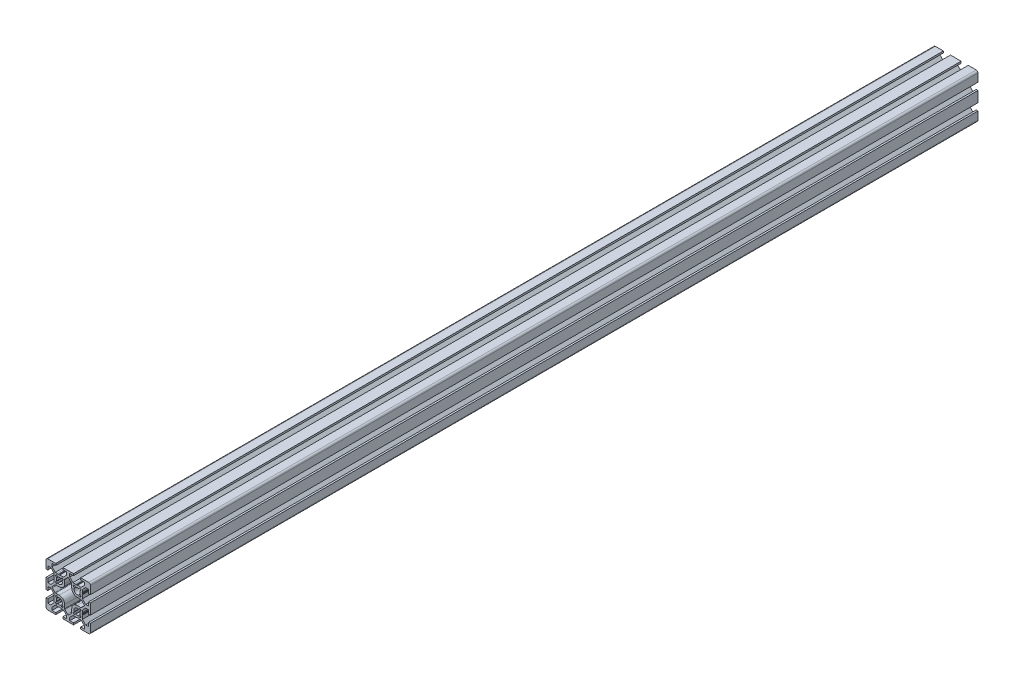
SolidWorks part; units mm, degrees
ref_plane "Front Plane" through (0, 0, 0) normal (0, 0, 1) x (1, 0, 0)
ref_plane "Top Plane" through (0, 0, 0) normal (0, 1, 0) x (1, 0, 0)
ref_plane "Right Plane" through (0, 0, 0) normal (1, 0, 0) x (0, 0, -1)
ref_plane "Plane1" through (0, 0, 0) normal (0, 0, 1) x (1, 0, 0)
sketch "Sketch1" plane through (0, 0, 0) normal (0, 0, 1) x (1, 0, 0)
  line L0 (-25, 23) -> (-25, 14)
  line L1 (-25, 14) -> (-23, 14)
  line L2 (-23, 14) -> (-23, 18.25)
  line L3 (-23, 18.25) -> (-19.6642, 18.25)
  line L4 (-19.6642, 18.25) -> (-16, 14.5858)
  line L5 (-16, 14.5858) -> (-16, 10.6536)
  line L6 (-15.933, 10.4036) -> (-15.7, 10)
  line L7 (-15.7, 10) -> (-15.933, 9.5964)
  line L8 (-15.933, 9.0964) -> (-15.751, 8.7811)
  line L9 (-15.751, 8.7811) -> (-16, 7.5)
  line L10 (-16, 7.5) -> (-16, 5.4142)
  line L11 (-16, 5.4142) -> (-19.6642, 1.75)
  line L12 (-19.6642, 1.75) -> (-23, 1.75)
  line L13 (-23, 1.75) -> (-23, 6)
  line L14 (-23, 6) -> (-25, 6)
  line L15 (-25, 6) -> (-25, -6)
  line L16 (-25, -6) -> (-23, -6)
  line L17 (-23, -6) -> (-23, -1.75)
  line L18 (-23, -1.75) -> (-19.6642, -1.75)
  line L19 (-19.6642, -1.75) -> (-16, -5.4142)
  line L20 (-16, -5.4142) -> (-16, -9.3464)
  line L21 (-15.933, -9.5964) -> (-15.7, -10)
  line L22 (-15.7, -10) -> (-15.933, -10.4036)
  line L23 (-15.933, -10.9036) -> (-15.751, -11.2189)
  line L24 (-15.751, -11.2189) -> (-16, -12.5)
  line L25 (-16, -12.5) -> (-16, -14.5858)
  line L26 (-16, -14.5858) -> (-19.6642, -18.25)
  line L27 (-19.6642, -18.25) -> (-23, -18.25)
  line L28 (-23, -18.25) -> (-23, -14)
  line L29 (-23, -14) -> (-25, -14)
  line L30 (-25, -14) -> (-25, -23)
  line L31 (-23, -25) -> (-14, -25)
  line L32 (-14, -25) -> (-14, -23)
  line L33 (-14, -23) -> (-18.25, -23)
  line L34 (-18.25, -23) -> (-18.25, -19.6642)
  line L35 (-18.25, -19.6642) -> (-14.5858, -16)
  line L36 (-14.5858, -16) -> (-10.6536, -16)
  line L37 (-10.4036, -15.933) -> (-10, -15.7)
  line L38 (-10, -15.7) -> (-9.5964, -15.933)
  line L39 (-9.0964, -15.933) -> (-8.7811, -15.751)
  line L40 (-8.7811, -15.751) -> (-7.5, -16)
  line L41 (-7.5, -16) -> (-5.4142, -16)
  line L42 (-5.4142, -16) -> (-1.75, -19.6642)
  line L43 (-1.75, -19.6642) -> (-1.75, -23)
  line L44 (-1.75, -23) -> (-6, -23)
  line L45 (-6, -23) -> (-6, -25)
  line L46 (-6, -25) -> (6, -25)
  line L47 (6, -25) -> (6, -23)
  line L48 (6, -23) -> (1.75, -23)
  line L49 (1.75, -23) -> (1.75, -19.6642)
  line L50 (1.75, -19.6642) -> (5.4142, -16)
  line L51 (5.4142, -16) -> (9.3464, -16)
  line L52 (9.5964, -15.933) -> (10, -15.7)
  line L53 (10, -15.7) -> (10.4036, -15.933)
  line L54 (10.9036, -15.933) -> (11.2189, -15.751)
  line L55 (11.2189, -15.751) -> (12.5, -16)
  line L56 (12.5, -16) -> (14.5858, -16)
  line L57 (14.5858, -16) -> (18.25, -19.6642)
  line L58 (18.25, -19.6642) -> (18.25, -23)
  line L59 (18.25, -23) -> (14, -23)
  line L60 (14, -23) -> (14, -25)
  line L61 (14, -25) -> (23, -25)
  line L62 (25, -23) -> (25, -14)
  line L63 (25, -14) -> (23, -14)
  line L64 (23, -14) -> (23, -18.25)
  line L65 (23, -18.25) -> (19.6642, -18.25)
  line L66 (19.6642, -18.25) -> (16, -14.5858)
  line L67 (16, -14.5858) -> (16, -10.6536)
  line L68 (15.933, -10.4036) -> (15.7, -10)
  line L69 (15.7, -10) -> (15.933, -9.5964)
  line L70 (15.933, -9.0964) -> (15.751, -8.7811)
  line L71 (15.751, -8.7811) -> (16, -7.5)
  line L72 (16, -7.5) -> (16, -5.4142)
  line L73 (16, -5.4142) -> (19.6642, -1.75)
  line L74 (19.6642, -1.75) -> (23, -1.75)
  line L75 (23, -1.75) -> (23, -6)
  line L76 (23, -6) -> (25, -6)
  line L77 (25, -6) -> (25, 6)
  line L78 (25, 6) -> (23, 6)
  line L79 (23, 6) -> (23, 1.75)
  line L80 (23, 1.75) -> (19.6642, 1.75)
  line L81 (19.6642, 1.75) -> (16, 5.4142)
  line L82 (16, 5.4142) -> (16, 9.3464)
  line L83 (15.933, 9.5964) -> (15.7, 10)
  line L84 (15.7, 10) -> (15.933, 10.4036)
  line L85 (15.933, 10.9036) -> (15.751, 11.2189)
  line L86 (15.751, 11.2189) -> (16, 12.5)
  line L87 (16, 12.5) -> (16, 14.5858)
  line L88 (16, 14.5858) -> (19.6642, 18.25)
  line L89 (19.6642, 18.25) -> (23, 18.25)
  line L90 (23, 18.25) -> (23, 14)
  line L91 (23, 14) -> (25, 14)
  line L92 (25, 14) -> (25, 23)
  line L93 (23, 25) -> (14, 25)
  line L94 (14, 25) -> (14, 23)
  line L95 (14, 23) -> (18.25, 23)
  line L96 (18.25, 23) -> (18.25, 19.6642)
  line L97 (18.25, 19.6642) -> (14.5858, 16)
  line L98 (14.5858, 16) -> (10.6536, 16)
  line L99 (10.4036, 15.933) -> (10, 15.7)
  line L100 (10, 15.7) -> (9.5964, 15.933)
  line L101 (9.0964, 15.933) -> (8.7811, 15.751)
  line L102 (8.7811, 15.751) -> (7.5, 16)
  line L103 (7.5, 16) -> (5.4142, 16)
  line L104 (5.4142, 16) -> (1.75, 19.6642)
  line L105 (1.75, 19.6642) -> (1.75, 23)
  line L106 (1.75, 23) -> (6, 23)
  line L107 (6, 23) -> (6, 25)
  line L108 (6, 25) -> (-6, 25)
  line L109 (-6, 25) -> (-6, 23)
  line L110 (-6, 23) -> (-1.75, 23)
  line L111 (-1.75, 23) -> (-1.75, 19.6642)
  line L112 (-1.75, 19.6642) -> (-5.4142, 16)
  line L113 (-5.4142, 16) -> (-9.3464, 16)
  line L114 (-9.5964, 15.933) -> (-10, 15.7)
  line L115 (-10, 15.7) -> (-10.4036, 15.933)
  line L116 (-10.9036, 15.933) -> (-11.2189, 15.751)
  line L117 (-11.2189, 15.751) -> (-12.5, 16)
  line L118 (-12.5, 16) -> (-14.5858, 16)
  line L119 (-14.5858, 16) -> (-18.25, 19.6642)
  line L120 (-18.25, 19.6642) -> (-18.25, 23)
  line L121 (-18.25, 23) -> (-14, 23)
  line L122 (-14, 23) -> (-14, 25)
  line L123 (-14, 25) -> (-23, 25)
  line L124 (-17.8787, -0.7071) -> (-14.8787, -3.7071)
  line L125 (-14.1716, -4) -> (-10, -4)
  line L126 (-4, -10) -> (-4, -14.1716)
  line L127 (-3.7071, -14.8787) -> (-0.7071, -17.8787)
  line L128 (0.7071, -17.8787) -> (3.7071, -14.8787)
  line L129 (4, -14.1716) -> (4, -10)
  line L130 (10, -4) -> (14.1716, -4)
  line L131 (14.8787, -3.7071) -> (17.8787, -0.7071)
  line L132 (17.8787, 0.7071) -> (14.8787, 3.7071)
  line L133 (14.1716, 4) -> (10, 4)
  line L134 (4, 10) -> (4, 14.1716)
  line L135 (3.7071, 14.8787) -> (0.7071, 17.8787)
  line L136 (-0.7071, 17.8787) -> (-3.7071, 14.8787)
  line L137 (-4, 14.1716) -> (-4, 10)
  line L138 (-10, 4) -> (-14.1716, 4)
  line L139 (-14.8787, 3.7071) -> (-17.8787, 0.7071)
  arc A0 (-16, 10.6536) -> (-15.933, 10.4036) centre (-15.5, 10.6536) ccw
  arc A1 (-15.933, 9.5964) -> (-15.933, 9.0964) centre (-15.5, 9.3464) ccw
  arc A2 (-16, -9.3464) -> (-15.933, -9.5964) centre (-15.5, -9.3464) ccw
  arc A3 (-15.933, -10.4036) -> (-15.933, -10.9036) centre (-15.5, -10.6536) ccw
  arc A4 (-25, -23) -> (-23, -25) centre (-23, -23) ccw
  arc A5 (-10.6536, -16) -> (-10.4036, -15.933) centre (-10.6536, -15.5) ccw
  arc A6 (-9.5964, -15.933) -> (-9.0964, -15.933) centre (-9.3464, -15.5) ccw
  arc A7 (9.3464, -16) -> (9.5964, -15.933) centre (9.3464, -15.5) ccw
  arc A8 (10.4036, -15.933) -> (10.9036, -15.933) centre (10.6536, -15.5) ccw
  arc A9 (23, -25) -> (25, -23) centre (23, -23) ccw
  arc A10 (16, -10.6536) -> (15.933, -10.4036) centre (15.5, -10.6536) ccw
  arc A11 (15.933, -9.5964) -> (15.933, -9.0964) centre (15.5, -9.3464) ccw
  arc A12 (16, 9.3464) -> (15.933, 9.5964) centre (15.5, 9.3464) ccw
  arc A13 (15.933, 10.4036) -> (15.933, 10.9036) centre (15.5, 10.6536) ccw
  arc A14 (25, 23) -> (23, 25) centre (23, 23) ccw
  arc A15 (10.6536, 16) -> (10.4036, 15.933) centre (10.6536, 15.5) ccw
  arc A16 (9.5964, 15.933) -> (9.0964, 15.933) centre (9.3464, 15.5) ccw
  arc A17 (-9.3464, 16) -> (-9.5964, 15.933) centre (-9.3464, 15.5) ccw
  arc A18 (-10.4036, 15.933) -> (-10.9036, 15.933) centre (-10.6536, 15.5) ccw
  arc A19 (-23, 25) -> (-25, 23) centre (-23, 23) ccw
  arc A20 (-17.8787, 0.7071) -> (-17.8787, -0.7071) centre (-17.1716, 0) ccw
  arc A21 (-14.8787, -3.7071) -> (-14.1716, -4) centre (-14.1716, -3) ccw
  arc A22 (-10, -4) -> (-4, -10) centre (-10, -10) cw
  arc A23 (-4, -14.1716) -> (-3.7071, -14.8787) centre (-3, -14.1716) ccw
  arc A24 (-0.7071, -17.8787) -> (0.7071, -17.8787) centre (0, -17.1716) ccw
  arc A25 (3.7071, -14.8787) -> (4, -14.1716) centre (3, -14.1716) ccw
  arc A26 (4, -10) -> (10, -4) centre (10, -10) cw
  arc A27 (14.1716, -4) -> (14.8787, -3.7071) centre (14.1716, -3) ccw
  arc A28 (17.8787, -0.7071) -> (17.8787, 0.7071) centre (17.1716, 0) ccw
  arc A29 (14.8787, 3.7071) -> (14.1716, 4) centre (14.1716, 3) ccw
  arc A30 (10, 4) -> (4, 10) centre (10, 10) cw
  arc A31 (4, 14.1716) -> (3.7071, 14.8787) centre (3, 14.1716) ccw
  arc A32 (0.7071, 17.8787) -> (-0.7071, 17.8787) centre (0, 17.1716) ccw
  arc A33 (-3.7071, 14.8787) -> (-4, 14.1716) centre (-3, 14.1716) ccw
  arc A34 (-4, 10) -> (-10, 4) centre (-10, 10) cw
  arc A35 (-14.1716, 4) -> (-14.8787, 3.7071) centre (-14.1716, 3) ccw
extrude "Boss-Extrude1" add sketch "Sketch1" against normal blind 1000
ref_plane "Plane2" through (0, 0, 0) normal (0, 0, 1) x (1, 0, 0)
sketch "Sketch2" plane through (0, 0, 0) normal (0, 0, 1) x (1, 0, 0)
  line L0 (-14.2426, 12.8284) -> (-13.2051, 11.7909)
  line L1 (-13.2051, 8.2091) -> (-14.2426, 7.1716)
  line L2 (-14.2426, 6.4645) -> (-13.5355, 5.7574)
  line L3 (-12.8284, 5.7574) -> (-11.7909, 6.7949)
  line L4 (-6.7949, 11.7909) -> (-5.7574, 12.8284)
  line L5 (-5.7574, 13.5355) -> (-6.4645, 14.2426)
  line L6 (-7.1716, 14.2426) -> (-8.2091, 13.2051)
  line L7 (-11.7909, 13.2051) -> (-12.8284, 14.2426)
  line L8 (-13.5355, 14.2426) -> (-14.2426, 13.5355)
  arc A0 (-14.2426, 13.5355) -> (-14.2426, 12.8284) centre (-13.8891, 13.182) ccw
  arc A1 (-13.2051, 11.7909) -> (-13.1208, 11.3493) centre (-13.4879, 11.508) cw
  arc A2 (-13.1208, 11.3493) -> (-13.1208, 8.6507) centre (-10, 10) ccw
  arc A3 (-13.1208, 8.6507) -> (-13.2051, 8.2091) centre (-13.4879, 8.492) cw
  arc A4 (-14.2426, 7.1716) -> (-14.2426, 6.4645) centre (-13.8891, 6.818) ccw
  arc A5 (-13.5355, 5.7574) -> (-12.8284, 5.7574) centre (-13.182, 6.1109) ccw
  arc A6 (-11.7909, 6.7949) -> (-11.3493, 6.8792) centre (-11.508, 6.5121) cw
  arc A7 (-11.3493, 6.8792) -> (-6.8792, 11.3493) centre (-10, 10) ccw
  arc A8 (-6.8792, 11.3493) -> (-6.7949, 11.7909) centre (-6.5121, 11.508) cw
  arc A9 (-5.7574, 12.8284) -> (-5.7574, 13.5355) centre (-6.1109, 13.182) ccw
  arc A10 (-6.4645, 14.2426) -> (-7.1716, 14.2426) centre (-6.818, 13.8891) ccw
  arc A11 (-8.2091, 13.2051) -> (-8.6507, 13.1208) centre (-8.492, 13.4879) cw
  arc A12 (-8.6507, 13.1208) -> (-11.3493, 13.1208) centre (-10, 10) ccw
  arc A13 (-11.3493, 13.1208) -> (-11.7909, 13.2051) centre (-11.508, 13.4879) cw
  arc A14 (-12.8284, 14.2426) -> (-13.5355, 14.2426) centre (-13.182, 13.8891) ccw
extrude "Cut-Extrude1" cut sketch "Sketch2" against normal through all
ref_plane "Plane3" through (0, 0, 0) normal (0, 0, 1) x (1, 0, 0)
sketch "Sketch3" plane through (0, 0, 0) normal (0, 0, 1) x (1, 0, 0)
  line L0 (-12.8284, -14.2426) -> (-11.7909, -13.2051)
  line L1 (-8.2091, -13.2051) -> (-7.1716, -14.2426)
  line L2 (-6.4645, -14.2426) -> (-5.7574, -13.5355)
  line L3 (-5.7574, -12.8284) -> (-6.7949, -11.7909)
  line L4 (-11.7909, -6.7949) -> (-12.8284, -5.7574)
  line L5 (-13.5355, -5.7574) -> (-14.2426, -6.4645)
  line L6 (-14.2426, -7.1716) -> (-13.2051, -8.2091)
  line L7 (-13.2051, -11.7909) -> (-14.2426, -12.8284)
  line L8 (-14.2426, -13.5355) -> (-13.5355, -14.2426)
  arc A0 (-13.5355, -14.2426) -> (-12.8284, -14.2426) centre (-13.182, -13.8891) ccw
  arc A1 (-11.7909, -13.2051) -> (-11.3493, -13.1208) centre (-11.508, -13.4879) cw
  arc A2 (-11.3493, -13.1208) -> (-8.6507, -13.1208) centre (-10, -10) ccw
  arc A3 (-8.6507, -13.1208) -> (-8.2091, -13.2051) centre (-8.492, -13.4879) cw
  arc A4 (-7.1716, -14.2426) -> (-6.4645, -14.2426) centre (-6.818, -13.8891) ccw
  arc A5 (-5.7574, -13.5355) -> (-5.7574, -12.8284) centre (-6.1109, -13.182) ccw
  arc A6 (-6.7949, -11.7909) -> (-6.8792, -11.3493) centre (-6.5121, -11.508) cw
  arc A7 (-6.8792, -11.3493) -> (-11.3493, -6.8792) centre (-10, -10) ccw
  arc A8 (-11.3493, -6.8792) -> (-11.7909, -6.7949) centre (-11.508, -6.5121) cw
  arc A9 (-12.8284, -5.7574) -> (-13.5355, -5.7574) centre (-13.182, -6.1109) ccw
  arc A10 (-14.2426, -6.4645) -> (-14.2426, -7.1716) centre (-13.8891, -6.818) ccw
  arc A11 (-13.2051, -8.2091) -> (-13.1208, -8.6507) centre (-13.4879, -8.492) cw
  arc A12 (-13.1208, -8.6507) -> (-13.1208, -11.3493) centre (-10, -10) ccw
  arc A13 (-13.1208, -11.3493) -> (-13.2051, -11.7909) centre (-13.4879, -11.508) cw
  arc A14 (-14.2426, -12.8284) -> (-14.2426, -13.5355) centre (-13.8891, -13.182) ccw
extrude "Cut-Extrude2" cut sketch "Sketch3" against normal through all
ref_plane "Plane4" through (0, 0, 0) normal (0, 0, 1) x (1, 0, 0)
sketch "Sketch4" plane through (0, 0, 0) normal (0, 0, 1) x (1, 0, 0)
  line L0 (14.2426, -12.8284) -> (13.2051, -11.7909)
  line L1 (13.2051, -8.2091) -> (14.2426, -7.1716)
  line L2 (14.2426, -6.4645) -> (13.5355, -5.7574)
  line L3 (12.8284, -5.7574) -> (11.7909, -6.7949)
  line L4 (6.7949, -11.7909) -> (5.7574, -12.8284)
  line L5 (5.7574, -13.5355) -> (6.4645, -14.2426)
  line L6 (7.1716, -14.2426) -> (8.2091, -13.2051)
  line L7 (11.7909, -13.2051) -> (12.8284, -14.2426)
  line L8 (13.5355, -14.2426) -> (14.2426, -13.5355)
  arc A0 (14.2426, -13.5355) -> (14.2426, -12.8284) centre (13.8891, -13.182) ccw
  arc A1 (13.2051, -11.7909) -> (13.1208, -11.3493) centre (13.4879, -11.508) cw
  arc A2 (13.1208, -11.3493) -> (13.1208, -8.6507) centre (10, -10) ccw
  arc A3 (13.1208, -8.6507) -> (13.2051, -8.2091) centre (13.4879, -8.492) cw
  arc A4 (14.2426, -7.1716) -> (14.2426, -6.4645) centre (13.8891, -6.818) ccw
  arc A5 (13.5355, -5.7574) -> (12.8284, -5.7574) centre (13.182, -6.1109) ccw
  arc A6 (11.7909, -6.7949) -> (11.3493, -6.8792) centre (11.508, -6.5121) cw
  arc A7 (11.3493, -6.8792) -> (6.8792, -11.3493) centre (10, -10) ccw
  arc A8 (6.8792, -11.3493) -> (6.7949, -11.7909) centre (6.5121, -11.508) cw
  arc A9 (5.7574, -12.8284) -> (5.7574, -13.5355) centre (6.1109, -13.182) ccw
  arc A10 (6.4645, -14.2426) -> (7.1716, -14.2426) centre (6.818, -13.8891) ccw
  arc A11 (8.2091, -13.2051) -> (8.6507, -13.1208) centre (8.492, -13.4879) cw
  arc A12 (8.6507, -13.1208) -> (11.3493, -13.1208) centre (10, -10) ccw
  arc A13 (11.3493, -13.1208) -> (11.7909, -13.2051) centre (11.508, -13.4879) cw
  arc A14 (12.8284, -14.2426) -> (13.5355, -14.2426) centre (13.182, -13.8891) ccw
extrude "Cut-Extrude3" cut sketch "Sketch4" against normal through all
ref_plane "Plane5" through (0, 0, 0) normal (0, 0, 1) x (1, 0, 0)
sketch "Sketch5" plane through (0, 0, 0) normal (0, 0, 1) x (1, 0, 0)
  line L0 (12.8284, 14.2426) -> (11.7909, 13.2051)
  line L1 (8.2091, 13.2051) -> (7.1716, 14.2426)
  line L2 (6.4645, 14.2426) -> (5.7574, 13.5355)
  line L3 (5.7574, 12.8284) -> (6.7949, 11.7909)
  line L4 (11.7909, 6.7949) -> (12.8284, 5.7574)
  line L5 (13.5355, 5.7574) -> (14.2426, 6.4645)
  line L6 (14.2426, 7.1716) -> (13.2051, 8.2091)
  line L7 (13.2051, 11.7909) -> (14.2426, 12.8284)
  line L8 (14.2426, 13.5355) -> (13.5355, 14.2426)
  arc A0 (13.5355, 14.2426) -> (12.8284, 14.2426) centre (13.182, 13.8891) ccw
  arc A1 (11.7909, 13.2051) -> (11.3493, 13.1208) centre (11.508, 13.4879) cw
  arc A2 (11.3493, 13.1208) -> (8.6507, 13.1208) centre (10, 10) ccw
  arc A3 (8.6507, 13.1208) -> (8.2091, 13.2051) centre (8.492, 13.4879) cw
  arc A4 (7.1716, 14.2426) -> (6.4645, 14.2426) centre (6.818, 13.8891) ccw
  arc A5 (5.7574, 13.5355) -> (5.7574, 12.8284) centre (6.1109, 13.182) ccw
  arc A6 (6.7949, 11.7909) -> (6.8792, 11.3493) centre (6.5121, 11.508) cw
  arc A7 (6.8792, 11.3493) -> (11.3493, 6.8792) centre (10, 10) ccw
  arc A8 (11.3493, 6.8792) -> (11.7909, 6.7949) centre (11.508, 6.5121) cw
  arc A9 (12.8284, 5.7574) -> (13.5355, 5.7574) centre (13.182, 6.1109) ccw
  arc A10 (14.2426, 6.4645) -> (14.2426, 7.1716) centre (13.8891, 6.818) ccw
  arc A11 (13.2051, 8.2091) -> (13.1208, 8.6507) centre (13.4879, 8.492) cw
  arc A12 (13.1208, 8.6507) -> (13.1208, 11.3493) centre (10, 10) ccw
  arc A13 (13.1208, 11.3493) -> (13.2051, 11.7909) centre (13.4879, 11.508) cw
  arc A14 (14.2426, 12.8284) -> (14.2426, 13.5355) centre (13.8891, 13.182) ccw
extrude "Cut-Extrude4" cut sketch "Sketch5" against normal through all
